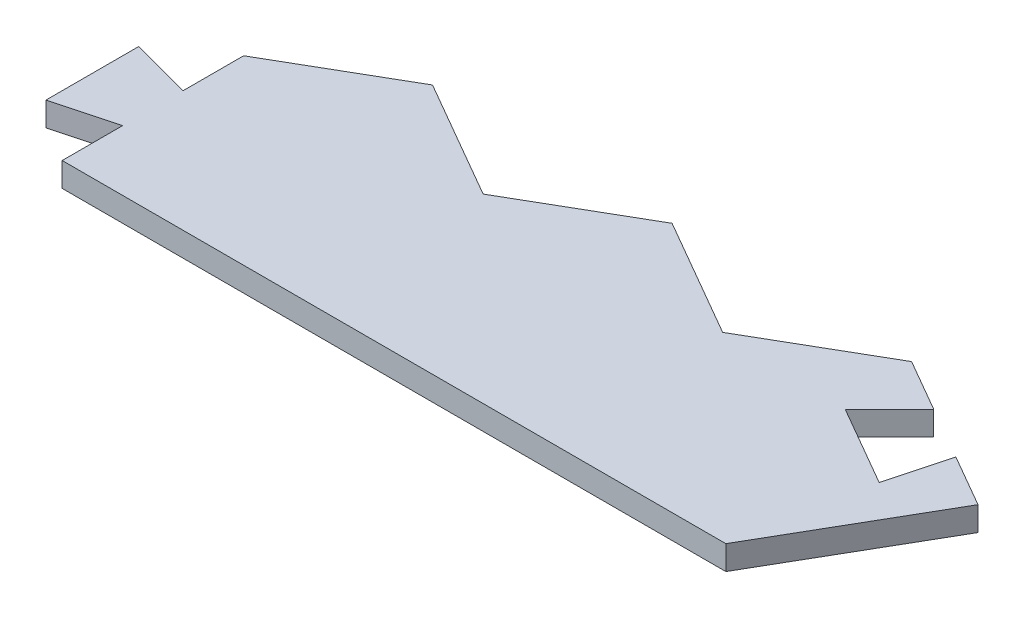
SolidWorks part; units mm, degrees
material "Teak"
ref_plane "Front Plane" through (0, 0, 0) normal (0, 0, 1) x (1, 0, 0)
ref_plane "Top Plane" through (0, 0, 0) normal (0, 1, 0) x (1, 0, 0)
ref_plane "Right Plane" through (0, 0, 0) normal (1, 0, 0) x (0, 0, -1)
sketch "Sketch1" plane through (0, 0, 0) normal (0, 1, 0) x (1, 0, 0)
  line L0 (0, 0) -> (219.497, 0)
  line L1 (0, 0) -> (0, 20)
  line L2 (0, 60) -> (39.612, 82.87)
  line L3 (39.612, 82.87) -> (79.224, 60)
  line L4 (79.224, 60) -> (118.836, 82.87)
  line L5 (118.836, 82.87) -> (158.448, 60)
  line L6 (158.448, 60) -> (198.06, 82.87)
  line L7 (219.497, 0) -> (250.0215, 52.87)
  line L8 (198.06, 82.87) -> (215.3805, 72.87)
  line L9 (0, 40) -> (-20, 45.359)
  line L10 (-20, 45.359) -> (-20, 14.641)
  line L11 (-20, 14.641) -> (0, 20)
  line L12 (215.3805, 72.87) -> (200.7395, 58.229)
  line L13 (200.7395, 58.229) -> (227.342, 42.87)
  line L14 (227.342, 42.87) -> (232.701, 62.87)
  line L15 (0, 40) -> (0, 60)
  line L16 (232.701, 62.87) -> (250.0215, 52.87)
  dimension "D1" = 60
  dimension "D2" = 120
  dimension "D3" = 120
  dimension "D4" = 120
  dimension "D5" = 120
  dimension "D6" = 45.74
  dimension "D7" = 45.74
  dimension "D8" = 120
  dimension "D9" = 120
  dimension "D10" = 120
  dimension "D11" = 60
  dimension "D12" = 75
  dimension "D13" = 20
  dimension "D14" = 20
  dimension "D15" = 20
  dimension "D16" = 75
  dimension "D17" = 20
  dimension "D18" = 20
  dimension "D19" = 75
  dimension "D20" = 20
  dimension "D21" = 75
extrude "Boss-Extrude1" add sketch "Sketch1" along normal blind 8
